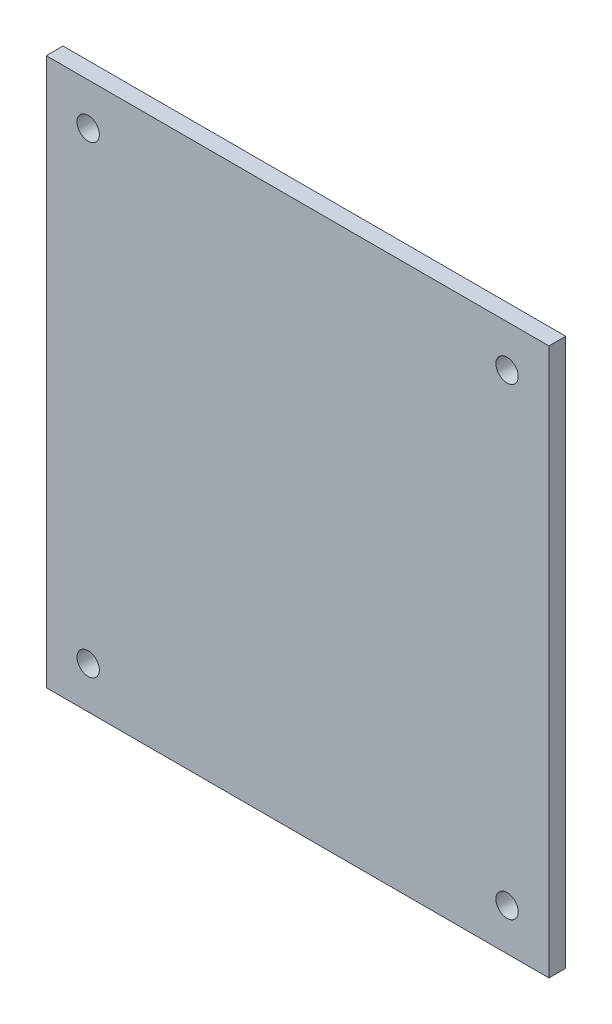
SolidWorks part; units mm, degrees
material "Copper"
ref_plane "Front Plane" through (0, 0, 0) normal (0, 0, 1) x (1, 0, 0)
ref_plane "Top Plane" through (0, 0, 0) normal (0, 1, 0) x (1, 0, 0)
ref_plane "Right Plane" through (0, 0, 0) normal (1, 0, 0) x (0, 0, -1)
sketch "Sketch2" plane through (0, 0, 0) normal (0, 0, 1) x (1, 0, 0)
  line L1 (22.5, 24.5) -> (-22.5, 24.5)
  line L2 (22.5, 24.5) -> (22.5, -24.5)
  line L3 (22.5, -24.5) -> (-22.5, -24.5)
  line L4 (-22.5, 24.5) -> (-22.5, -24.5)
  line L5 (22.5, 24.5) -> (-22.5, -24.5) construction
  line L6 (22.5, -24.5) -> (-22.5, 24.5) construction
  point P0 (0, 0)
  dimension "D1" = 45
  dimension "D2" = 49
extrude "Boss-Extrude1" add sketch "Sketch2" along normal blind 1.5
sketch "Sketch3" plane through (0, 0, 1.5) normal (0, 0, 1) x (1, 0, 0)
  line L0 (0, 24.5) -> (0, -24.5) construction
  line L1 (22.5, 24.5) -> (-22.5, 24.5) construction
  line L2 (-22.5, -24.5) -> (22.5, -24.5) construction
  line L3 (-22.5, 0) -> (22.5, 0) construction
  line L4 (-22.5, 24.5) -> (-22.5, -24.5) construction
  line L5 (22.5, -24.5) -> (22.5, 24.5) construction
  circle A0 centre (-18.75, 20.75) radius 1
  circle A1 centre (18.75, 20.75) radius 1
  circle A2 centre (18.75, -20.75) radius 1
  circle A3 centre (-18.75, -20.75) radius 1
  dimension "D1" = 2
  dimension "D2" = 3.75
  dimension "D3" = 3.75
extrude "Cut-Extrude1" cut sketch "Sketch3" against normal through all both and the other way through all
